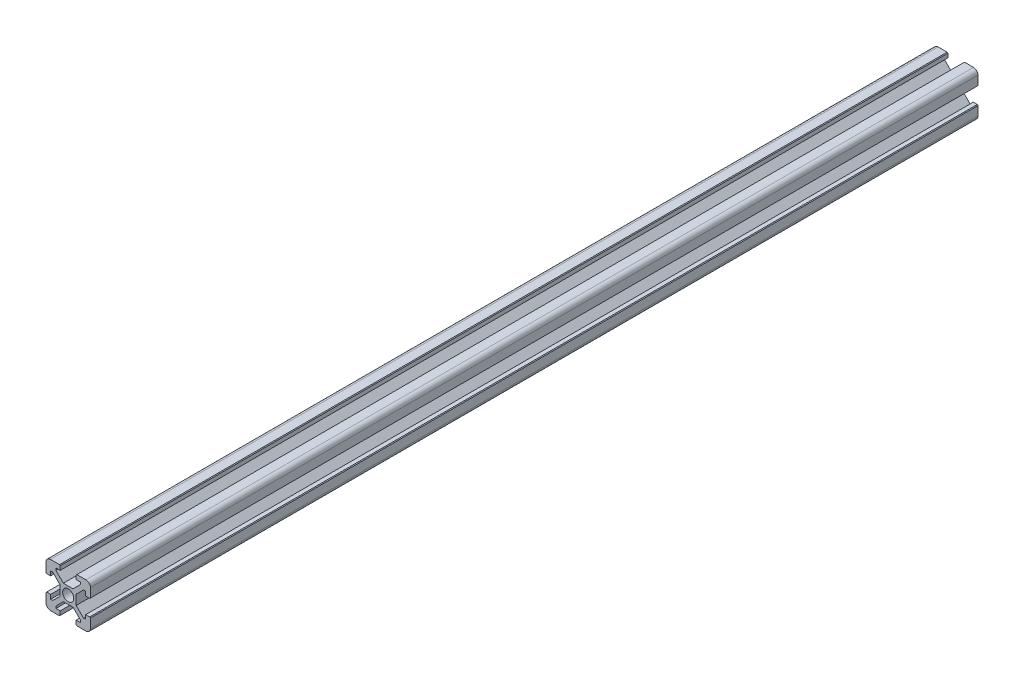
SolidWorks part; units mm, degrees
ref_plane "Front Plane" through (0, 0, 0) normal (0, 0, 1) x (1, 0, 0)
ref_plane "Top Plane" through (0, 0, 0) normal (0, 1, 0) x (1, 0, 0)
ref_plane "Right Plane" through (0, 0, 0) normal (1, 0, 0) x (0, 0, -1)
sketch "Sketch1" plane through (0, 0, 0) normal (0, 0, 1) x (1, 0, 0)
  line L0 (21.2215, -74.7547) -> (43.666, -74.7547) construction
  line L1 (19.0357, -71.1547) -> (23.4072, -71.1547)
  line L2 (23.4072, -71.1547) -> (26.7215, -67.8405)
  line L3 (26.7215, -67.8405) -> (26.7215, -66.8547)
  line L4 (26.7215, -66.8547) -> (24.8215, -66.8547)
  line L5 (24.8215, -66.8547) -> (24.8215, -65.0547)
  line L6 (25.1215, -64.7547) -> (29.2215, -64.7547)
  line L7 (31.2215, -66.7547) -> (31.2215, -70.8547)
  line L8 (30.9215, -71.1547) -> (29.1215, -71.1547)
  line L9 (28.1357, -69.2547) -> (29.1215, -69.2547)
  line L10 (28.1357, -69.2547) -> (24.8215, -72.5689)
  line L11 (24.8215, -72.5689) -> (24.8215, -76.9405)
  line L12 (29.1215, -69.2547) -> (29.1215, -71.1547)
  line L13 (31.2215, -70.8547) -> (30.9215, -71.1547)
  line L14 (24.8215, -65.0547) -> (25.1215, -64.7547)
  line L15 (17.6215, -72.5689) -> (17.6215, -76.9405)
  line L16 (14.3072, -69.2547) -> (17.6215, -72.5689)
  line L17 (14.3072, -69.2547) -> (13.3215, -69.2547)
  line L18 (13.3215, -69.2547) -> (13.3215, -71.1547)
  line L19 (11.5215, -71.1547) -> (13.3215, -71.1547)
  line L20 (11.2215, -70.8547) -> (11.5215, -71.1547)
  line L21 (11.2215, -66.7547) -> (11.2215, -70.8547)
  line L22 (17.3215, -64.7547) -> (13.2215, -64.7547)
  line L23 (17.6215, -65.0547) -> (17.3215, -64.7547)
  line L24 (17.6215, -66.8547) -> (17.6215, -65.0547)
  line L25 (15.7215, -66.8547) -> (17.6215, -66.8547)
  line L26 (15.7215, -67.8405) -> (15.7215, -66.8547)
  line L27 (19.0357, -71.1547) -> (15.7215, -67.8405)
  line L28 (28.1357, -80.2547) -> (24.8215, -76.9405)
  line L29 (28.1357, -80.2547) -> (29.1215, -80.2547)
  line L30 (29.1215, -80.2547) -> (29.1215, -78.3547)
  line L31 (30.9215, -78.3547) -> (29.1215, -78.3547)
  line L32 (31.2215, -78.6547) -> (30.9215, -78.3547)
  line L33 (31.2215, -82.7547) -> (31.2215, -78.6547)
  line L34 (25.1215, -84.7547) -> (29.2215, -84.7547)
  line L35 (24.8215, -84.4547) -> (25.1215, -84.7547)
  line L36 (24.8215, -82.6547) -> (24.8215, -84.4547)
  line L37 (26.7215, -82.6547) -> (24.8215, -82.6547)
  line L38 (26.7215, -81.6689) -> (26.7215, -82.6547)
  line L39 (23.4072, -78.3547) -> (26.7215, -81.6689)
  line L40 (19.0357, -78.3547) -> (23.4072, -78.3547)
  line L41 (19.0357, -78.3547) -> (15.7215, -81.6689)
  line L42 (15.7215, -81.6689) -> (15.7215, -82.6547)
  line L43 (15.7215, -82.6547) -> (17.6215, -82.6547)
  line L44 (17.6215, -82.6547) -> (17.6215, -84.4547)
  line L45 (17.6215, -84.4547) -> (17.3215, -84.7547)
  line L46 (17.3215, -84.7547) -> (13.2215, -84.7547)
  line L47 (11.2215, -82.7547) -> (11.2215, -78.6547)
  line L48 (11.2215, -78.6547) -> (11.5215, -78.3547)
  line L49 (11.5215, -78.3547) -> (13.3215, -78.3547)
  line L50 (13.3215, -80.2547) -> (13.3215, -78.3547)
  line L51 (14.3072, -80.2547) -> (13.3215, -80.2547)
  line L52 (14.3072, -80.2547) -> (17.6215, -76.9405)
  circle A0 centre (21.2215, -74.7547) radius 2.5
  arc A1 (31.2215, -66.7547) -> (29.2215, -64.7547) centre (29.2215, -66.7547) ccw
  arc A2 (11.2215, -66.7547) -> (13.2215, -64.7547) centre (13.2215, -66.7547) cw
  arc A3 (31.2215, -82.7547) -> (29.2215, -84.7547) centre (29.2215, -82.7547) cw
  arc A4 (11.2215, -82.7547) -> (13.2215, -84.7547) centre (13.2215, -82.7547) ccw
  point P8 (24.8215, -64.7547)
  point P10 (31.2215, -71.1547)
  point P37 (21.2215, -71.1547)
  point P38 (24.8215, -74.7547)
  point P67 (17.6215, -74.7547)
  dimension "D8" = 2
  dimension "D13" = 5
  dimension "D1" = 5.5
  dimension "D2" = 4.3
  dimension "D3" = 3.6
  dimension "D4" = 10
  dimension "D5" = 4.3
  dimension "D6" = 135
  dimension "D7" = 3.6
  dimension "D9" = 0.3
  dimension "D10" = 0.3
  dimension "D11" = 0.3
  dimension "D12" = 0.3
extrude "Boss-Extrude1" add sketch "Sketch1" against normal blind 400
